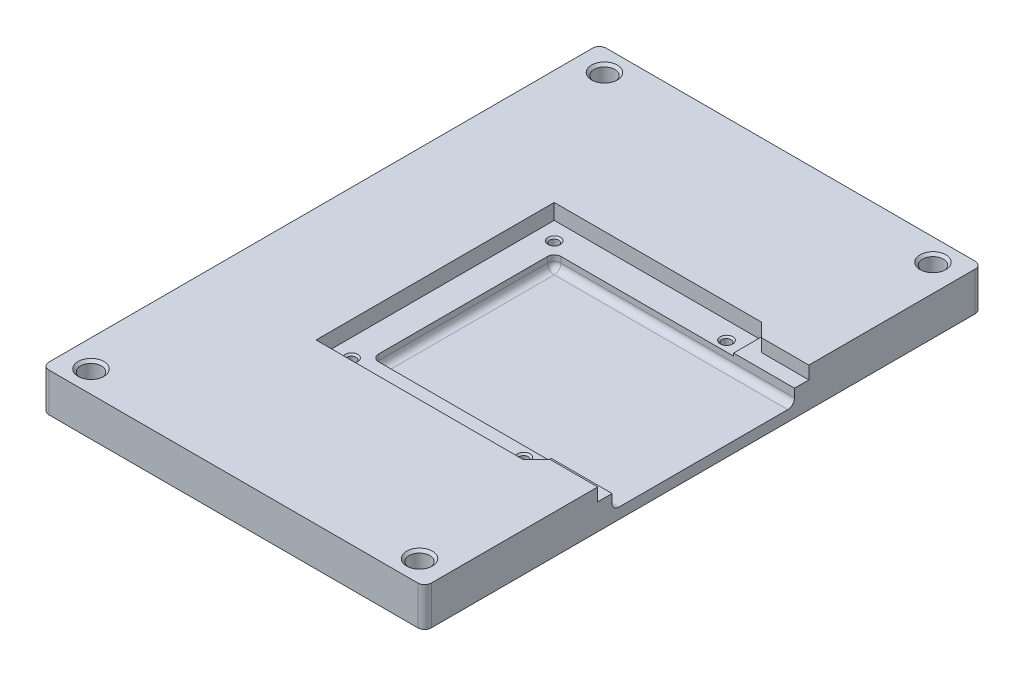
SolidWorks part; units mm, degrees
ref_plane "Front Plane" through (0, 0, 0) normal (0, 0, 1) x (1, 0, 0)
ref_plane "Top Plane" through (0, 0, 0) normal (0, 1, 0) x (1, 0, 0)
ref_plane "Right Plane" through (0, 0, 0) normal (1, 0, 0) x (0, 0, -1)
sketch "Sketch1" plane through (0, 0, 0) normal (0, 1, 0) x (1, 0, 0)
  line L0 (0, -67.5) -> (0, 67.5) construction
  line L1 (56.625, 67.5) -> (-56.625, 67.5) construction
  line L2 (-56.625, 67.5) -> (-56.625, -67.5)
  line L3 (-56.625, 0) -> (56.625, 0) construction
  line L4 (-56.625, 67.5) -> (-56.625, 80.5)
  line L5 (-54.625, 82.5) -> (54.625, 82.5)
  line L6 (0, 82.5) -> (0, 67.5) construction
  line L7 (56.625, 67.5) -> (56.625, 80.5)
  line L8 (56.625, 67.5) -> (56.625, -67.5)
  line L9 (0, -82.5) -> (0, -67.5) construction
  line L10 (56.625, -67.5) -> (-56.625, -67.5) construction
  line L11 (56.625, -67.5) -> (56.625, -80.5)
  line L12 (-54.625, -82.5) -> (54.625, -82.5)
  line L13 (-56.625, -67.5) -> (-56.625, -80.5)
  line L14 (-56.625, 70.5) -> (56.625, 70.5) construction
  circle A1 centre (-48.625, 76) radius 3.075 construction
  circle A2 centre (48.625, 76) radius 3.075 construction
  circle A5 centre (48.625, -76) radius 3.075 construction
  circle A6 centre (-48.625, -76) radius 3.075 construction
  arc A8 (-54.625, -82.5) -> (-56.625, -80.5) centre (-54.625, -80.5) cw
  arc A9 (56.625, -80.5) -> (54.625, -82.5) centre (54.625, -80.5) cw
  arc A10 (56.625, 80.5) -> (54.625, 82.5) centre (54.625, 80.5) ccw
  arc A11 (-56.625, 80.5) -> (-54.625, 82.5) centre (-54.625, 80.5) cw
  point P24 (0, 0)
  point P36 (-56.625, -82.5)
  point P39 (56.625, -82.5)
  point P42 (56.625, 82.5)
  point P45 (-56.625, 82.5)
  dimension "D10" = 2
  dimension "D3" = 6.15
  dimension "D1" = 56.625
  dimension "D2" = 67.5
  dimension "D4" = 6.5
  dimension "D6" = 8
  dimension "D7" = 8.5
  dimension "D8" = 12
  dimension "D9" = 3
  dimension "D11" = 82.5
extrude "Boss-Extrude1" add sketch "Sketch1" along normal blind 11.5
sketch "Sketch3" plane through (0, 11.5, 0) normal (0, 1, 0) x (1, 0, 0)
  line L0 (0, 0) -> (-56.625, 0) construction
  line L1 (-56.625, 80.5) -> (-56.625, -80.5) construction
  line L2 (0, 0) -> (0, 82.5) construction
  line L3 (54.625, 82.5) -> (-54.625, 82.5) construction
  line L4 (3.96, -16.3) -> (3.96, 16.3)
  line L5 (-2.46, -17.8) -> (2.46, -17.8)
  line L6 (-3.96, 16.3) -> (-3.96, -16.3)
  line L7 (2.46, 17.8) -> (-2.46, 17.8)
  line L8 (0, 17.8) -> (0, -17.8) construction
  line L9 (13.25, 0) -> (0, 0) construction
  line L10 (16.15, 10.025) -> (10.35, 10.025)
  line L11 (16.15, 10.025) -> (16.15, -10.025)
  line L12 (16.15, -10.025) -> (10.35, -10.025)
  line L13 (10.35, 10.025) -> (10.35, -10.025)
  line L14 (16.15, 10.025) -> (10.35, -10.025) construction
  line L15 (16.15, -10.025) -> (10.35, 10.025) construction
  line L16 (13.25, 0) -> (13.25, 10.025) construction
  line L17 (-16.15, 10.025) -> (-16.15, -10.025)
  line L18 (-16.15, -10.025) -> (-10.35, -10.025)
  line L23 (-16.15, 10.025) -> (-10.35, 10.025)
  line L24 (-10.35, 10.025) -> (-10.35, -10.025)
  arc A0 (-2.46, 17.8) -> (-3.96, 16.3) centre (-2.46, 16.3) ccw
  arc A1 (3.96, 16.3) -> (2.46, 17.8) centre (2.46, 16.3) ccw
  arc A2 (2.46, -17.8) -> (3.96, -16.3) centre (2.46, -16.3) ccw
  arc A3 (-3.96, -16.3) -> (-2.46, -17.8) centre (-2.46, -16.3) ccw
  point P9 (0, 0)
  point P23 (0, 0)
  dimension "D2" = 1.5
  dimension "D1" = 35.6
  dimension "D3" = 7.92
  dimension "D4" = 20.05
  dimension "D5" = 5.8
  dimension "D6" = 13.25
sketch "Sketch4" plane through (0, 11.5, 0) normal (0, 1, 0) x (1, 0, 0)
  circle A0 centre (-48.625, -76) radius 3.075 construction
  circle A1 centre (48.625, -76) radius 3.075 construction
  circle A2 centre (48.625, 76) radius 3.075 construction
  circle A5 centre (-48.625, 76) radius 3.075 construction
  circle A8 centre (-48.625, -76) radius 3.075
  circle A9 centre (48.625, -76) radius 3.075
  circle A10 centre (48.625, 76) radius 3.075
  circle A13 centre (-48.625, 76) radius 3.075
extrude "Cut-Extrude1" cut sketch "Sketch4" against normal blind 6
sketch "Sketch21" plane through (0, 11.5, 0) normal (0, 1, 0) x (1, 0, 0)
  line L0 (38.5, 35) -> (-22.5, 35) construction
  line L1 (38.5, 35) -> (42.5, 31) construction
  line L2 (-22.5, 35) -> (-22.5, -35) construction
  line L3 (-22.5, 0) -> (0, 0) construction
  line L4 (0, 0) -> (38.5, 0) construction
  line L5 (38.5, -35) -> (38.5, 35) construction
  line L6 (38.5, -35) -> (-22.5, -35) construction
  line L7 (42.5, 31) -> (56.625, 31) construction
  line L8 (56.625, -80.5) -> (56.625, 80.5) construction
  line L9 (56.625, 31) -> (56.625, -31)
  line L10 (56.625, 0) -> (38.5, 0) construction
  line L11 (42.5, -31) -> (56.625, -31) construction
  line L12 (38.5, -35) -> (42.5, -31) construction
  line L13 (42.6036, 31.25) -> (56.625, 31.25)
  line L14 (38.6036, 35.25) -> (42.6036, 31.25)
  line L15 (38.6036, 35.25) -> (-22.75, 35.25)
  line L16 (-22.75, 35.25) -> (-22.75, -35.25)
  line L17 (38.6036, -35.25) -> (-22.75, -35.25)
  line L18 (38.6036, -35.25) -> (42.6036, -31.25)
  line L19 (42.6036, -31.25) -> (56.625, -31.25)
  line L20 (56.625, -31.25) -> (56.625, -31)
  line L21 (56.625, 31) -> (56.625, 31.25)
  circle A0 centre (-17.5, 30) radius 1.6 construction
  circle A1 centre (33.5, 30) radius 1.6 construction
  circle A2 centre (33.5, -30) radius 1.6 construction
  circle A3 centre (-17.5, -30) radius 1.6 construction
  dimension "D8" = 3.2
  dimension "D1" = 22.5
  dimension "D2" = 61
  dimension "D3" = 35
  dimension "D4" = 5
  dimension "D5" = 5
  dimension "D6" = 5
  dimension "D7" = 5
  dimension "D9" = 45
  dimension "D10" = 4
  dimension "D12" = 14.125
  dimension "D11" = 0.25
extrude "Cut-Extrude6" cut sketch "Sketch21" against normal blind 4.6
sketch "Sketch24" plane through (0, 6.9, 0) normal (0, 1, 0) x (1, 0, 0)
  line L0 (56.625, 27) -> (-14.5, 27)
  line L2 (-14.5, 27) -> (-14.5, -27)
  line L3 (-14.5, -27) -> (56.625, -27)
  line L4 (56.625, -27) -> (56.625, 27)
  line L8 (38.5, 35) -> (-22.5, 35) construction
  line L10 (-22.5, 35) -> (-22.5, -35) construction
  line L11 (38.5, -35) -> (-22.5, -35) construction
  line L12 (56.625, -31.25) -> (56.625, 31.25) construction
  dimension "D1" = 8
  dimension "D2" = 8
  dimension "D3" = 8
extrude "Cut-Extrude3" cut sketch "Sketch24" against normal blind 3.7 and the other way through all
sketch "Sketch25" plane through (0, 6.9, 0) normal (0, 1, 0) x (1, 0, 0)
  circle A0 centre (33.5, 30) radius 1.35
  circle A1 centre (-17.5, 30) radius 1.35
  circle A2 centre (33.5, -30) radius 1.35
  circle A3 centre (-17.5, -30) radius 1.35
  dimension "D1" = 2.7
extrude "Cut-Extrude4" cut sketch "Sketch25" against normal blind 5
chamfer "Chamfer4" distance 0.5 angle 45 4 edges at (-17.5, 6.9, 31.35) (33.5, 6.9, 31.35) (33.5, 6.9, -28.65) (-17.5, 6.9, -28.65)
fillet "Fillet1" radius 2 5 edges at (21.0625, 3.2, 27) (-14.5, 5.05, 27) (-14.5, 5.05, -27) (-14.5, 3.2, 0) (21.0625, 3.2, -27)
sketch "Sketch26" plane through (0, 6.9, 0) normal (0, 1, 0) x (1, 0, 0)
  line L0 (0, 0) -> (56.625, 0) construction
  line L1 (56.625, -25) -> (56.625, 25) construction
  line L2 (38.6036, 35.25) -> (38.6036, 27)
  line L3 (56.625, 27) -> (-12.5, 27) construction
  line L4 (38.6036, 27) -> (56.625, 27)
  line L5 (56.625, 27) -> (56.625, 31.25)
  line L6 (56.625, 31.25) -> (42.6036, 31.25)
  line L7 (42.6036, 31.25) -> (38.6036, 35.25)
  line L8 (42.6036, -31.25) -> (38.6036, -35.25)
  line L9 (56.625, -31.25) -> (42.6036, -31.25)
  line L10 (56.625, -27) -> (56.625, -31.25)
  line L11 (38.6036, -27) -> (56.625, -27)
  line L12 (38.6036, -35.25) -> (38.6036, -27)
extrude "Boss-Extrude2" add sketch "Sketch26" along normal blind 0.8
chamfer "Chamfer5" distance 0.75 angle 45 4 edges at (48.625, 11.5, 79.075) (-48.625, 11.5, 79.075) (-48.625, 11.5, -72.925) (48.625, 11.5, -72.925)
equation "\"D5@Sketch21\"=\"D4@Sketch21\""
equation "\"D6@Sketch21\"=\"D4@Sketch21\""
equation "\"D7@Sketch21\"=\"D4@Sketch21\""
equation "\"D2@Sketch24\"=\"D1@Sketch24\""
equation "\"D3@Sketch24\"=\"D1@Sketch24\""
